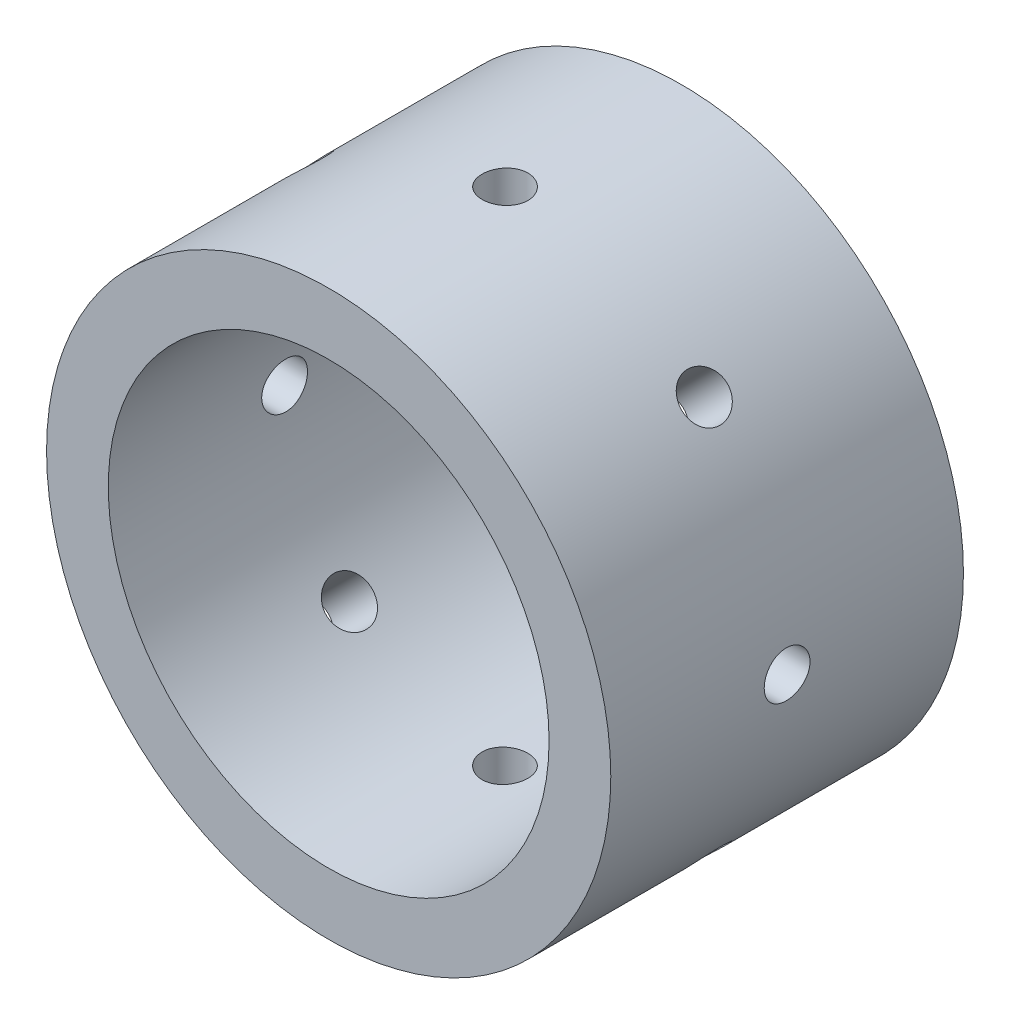
SolidWorks part; units mm, degrees
ref_plane "Front Plane" through (0, 0, 0) normal (0, 0, 1) x (1, 0, 0)
ref_plane "Top Plane" through (0, 0, 0) normal (0, 1, 0) x (1, 0, 0)
ref_plane "Right Plane" through (0, 0, 0) normal (1, 0, 0) x (0, 0, -1)
sketch "Sketch1" plane through (0, 0, 0) normal (0, 0, 1) x (1, 0, 0)
  circle A1 centre (0, 0) radius 20.32
  circle A2 centre (0, 0) radius 15.875
  dimension "D1" = 31.75
  dimension "D2" = 40.64
extrude "Boss-Extrude1" add sketch "Sketch1" along normal mid plane 25.4
hole_wizard "M4x0.7 Tapped Hole1" positions "Sketch2" profile "Sketch3" tap size "M4x0.7" standard "ANSI Metric"
sketch "Sketch2" plane through (0, 0, 0) normal (0, 1, 0) x (1, 0, 0)
  point P0 (0, 0)
  point P3 (0, 0)
sketch "Sketch3" plane through (0, 0, 0) normal (1, 0, 0) x (0, 0, -1)
  line L0 (0, 0) -> (0, 28.7368)
  line L1 (0, 28.7368) -> (1.65, 28.7368)
  line L2 (1.65, 28.7368) -> (1.65, 0)
  line L5 (1.65, 0) -> (0, 0)
  line L11 (0, -6.35) -> (0, 107.95) construction
  dimension "Thru Tap Drill Dia." = 3.3
  dimension "Thru Tap Drill Depth" = 28.7368
cosmetic thread "Hole Thread1" parameters "D1"=0, "D2"=4.3
pattern_circular "CirPattern1" count 8 over 360 about axis through (0, 0, 12.7) along (0, 0, -1) of "M4x0.7 Tapped Hole1"
